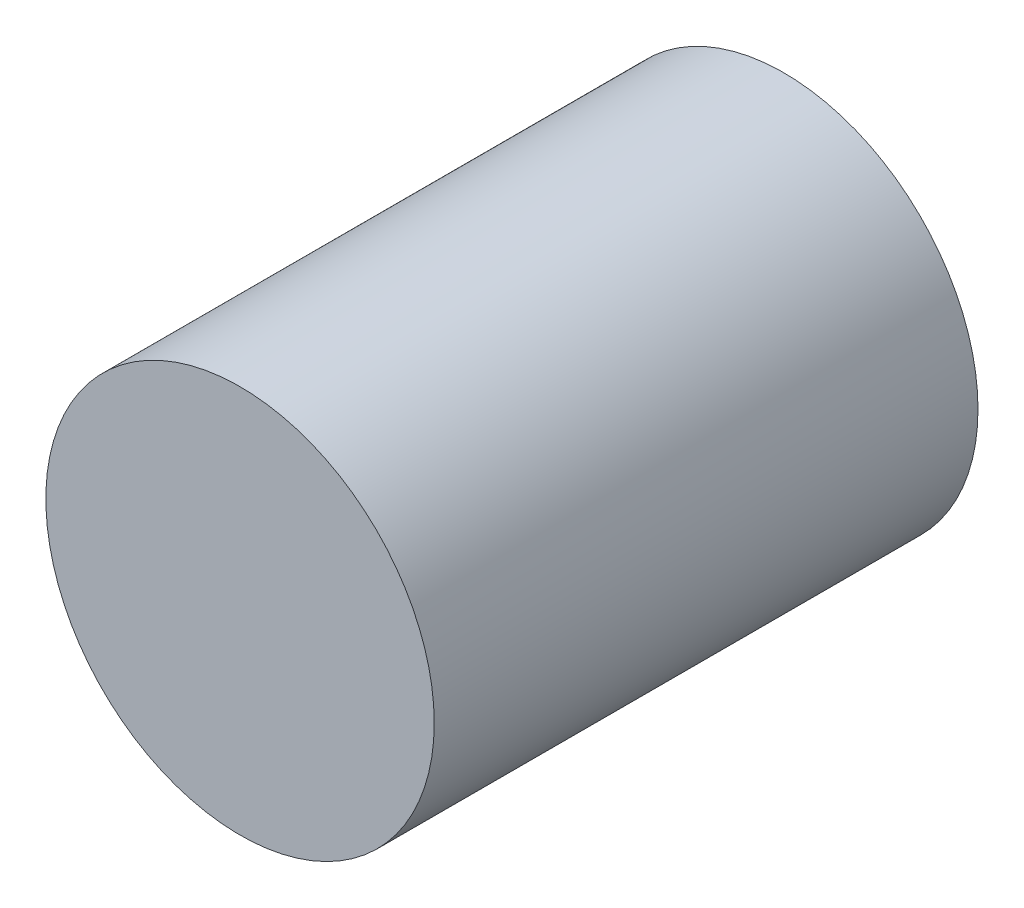
SolidWorks part; units mm, degrees
ref_plane "Front Plane" through (0, 0, 0) normal (0, 0, 1) x (1, 0, 0)
ref_plane "Top Plane" through (0, 0, 0) normal (0, 1, 0) x (1, 0, 0)
ref_plane "Right Plane" through (0, 0, 0) normal (1, 0, 0) x (0, 0, -1)
sketch "Sketch1" plane through (0, 0, 0) normal (0, 0, 1) x (1, 0, 0)
  circle A0 centre (0, 0) radius 50
  dimension "D1" = 100
extrude "Boss-Extrude1" add sketch "Sketch1" along normal mid plane 140
sketch "Sketch2" plane through (0, 0, -70) normal (0, 0, -1) x (-1, 0, 0)
  circle A0 centre (0, 0) radius 30
  dimension "D1" = 60
extrude "Cut-Extrude1" cut sketch "Sketch2" against normal blind 40
sketch "Sketch3" plane through (0, 0, -30) normal (0, 0, -1) x (-1, 0, 0)
  circle A0 centre (0, 0) radius 10
  dimension "D1" = 20
extrude "Cut-Extrude2" cut sketch "Sketch3" against normal blind 80
